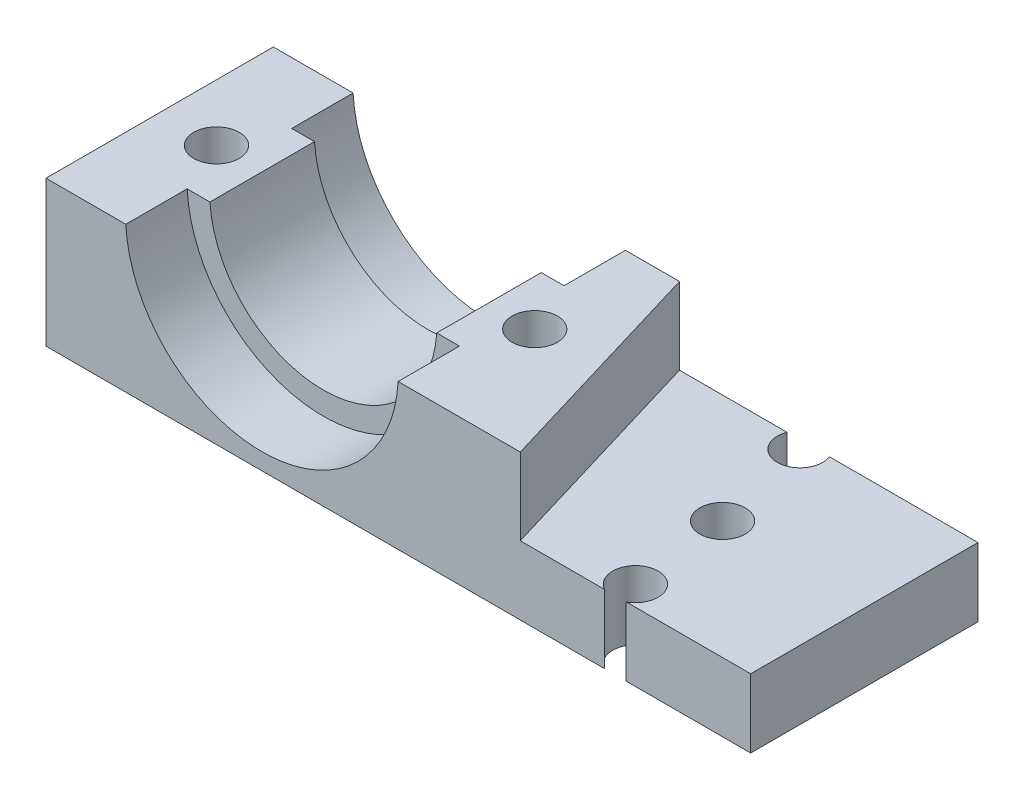
SolidWorks part; units mm, degrees
material "Nylon 6/10"
ref_plane "Front Plane" through (0, 0, 0) normal (0, 0, 1) x (1, 0, 0)
ref_plane "Top Plane" through (0, 0, 0) normal (0, 1, 0) x (1, 0, 0)
ref_plane "Right Plane" through (0, 0, 0) normal (1, 0, 0) x (0, 0, -1)
sketch "Sketch1" plane through (0, 0, 0) normal (1, 0, 0) x (0, 0, -1)
  line L0 (-25, 16) -> (25, 16)
  line L1 (-25, 16) -> (-25, -16)
  line L2 (25, 16) -> (25, -16)
  line L3 (-25, -16) -> (25, -16)
  line L4 (-25, 16) -> (25, -16) construction
  line L5 (25, 16) -> (-25, -16) construction
  point P1 (0, 0)
  dimension "D1" = 50
  dimension "D2" = 32
extrude "Boss-Extrude1" add sketch "Sketch1" along normal mid plane 95
sketch "Sketch3" plane through (0, 0, 0) normal (1, 0, 0) x (0, 0, -1)
  line L0 (-25, -12.35) -> (-11.5, -12.35)
  line L1 (-11.5, -12.35) -> (-11.5, -7.35)
  line L2 (-11.5, -7.35) -> (11.5, -7.35)
  line L3 (11.5, -7.35) -> (11.5, -12.35)
  line L4 (11.5, -12.35) -> (25, -12.35)
  line L5 (25, -12.35) -> (25, 16.5959)
  line L6 (25, 16.5959) -> (-25, 16.5959)
  line L7 (-25, 16.5959) -> (-25, -12.35)
  line L8 (20.2491, 17.65) -> (85.4, 17.65) construction
  line L9 (25, -16) -> (25, 16) construction
  line L10 (-25, 16) -> (-25, -16) construction
  line L13 (-25, -16) -> (25, -16) construction
  dimension "D1" = 33.65
  dimension "D2" = 30
  dimension "D3" = 23
  dimension "D4" = 50
revolve "Cut-Revolve1" cut sketch "Sketch3" angle 360 about L8
sketch "Sketch5" plane through (47.5, 0, 0) normal (1, 0, 0) x (0, 0, -1)
  line L4 (-25, 16) -> (-25, -16)
  line L5 (-25, -16) -> (25, -16)
  line L6 (25, -16) -> (25, 16)
  line L7 (25, 16) -> (-25, 16)
  line L8 (-25, 16) -> (-25, -16)
  line L9 (-25, -16) -> (25, -16)
  line L10 (25, -16) -> (25, 16)
  line L11 (25, 16) -> (-25, 16)
  dimension "D1" = 0
extrude "Boss-Extrude2" add sketch "Sketch5" along normal blind 60
sketch "Sketch4" plane through (0, 16, 0) normal (0, 1, 0) x (1, 0, 0)
  line L0 (-35, 0) -> (35, 0) construction
  circle A0 centre (-35, 0) radius 5
  circle A1 centre (35, 0) radius 5
  circle A2 centre (77.75, -20.6) radius 5
  circle A3 centre (75.2959, 1.0111) radius 5
  circle A4 centre (70.164, 23.1884) radius 5
  point P4 (0, 0)
  dimension "D2" = 10
  dimension "D1" = 70
extrude "Cut-Extrude1" cut sketch "Sketch4" against normal blind 75
sketch "Sketch6" plane through (0, 16, 0) normal (0, 1, 0) x (1, 0, 0)
  line L0 (97.4112, -160.4202) -> (40, 31.15)
  line L1 (97.4112, -160.4202) -> (161.2207, -141.2972)
  line L2 (40, 31.15) -> (103.8096, 50.2729)
  line L3 (161.2207, -141.2972) -> (103.8096, 50.2729)
  line L4 (97.4112, -160.4202) -> (103.8096, 50.2729) construction
  line L5 (40, 31.15) -> (161.2207, -141.2972) construction
  point P1 (100.6104, -55.0736)
extrude "Cut-Extrude2" cut sketch "Sketch6" against normal blind 16.9
